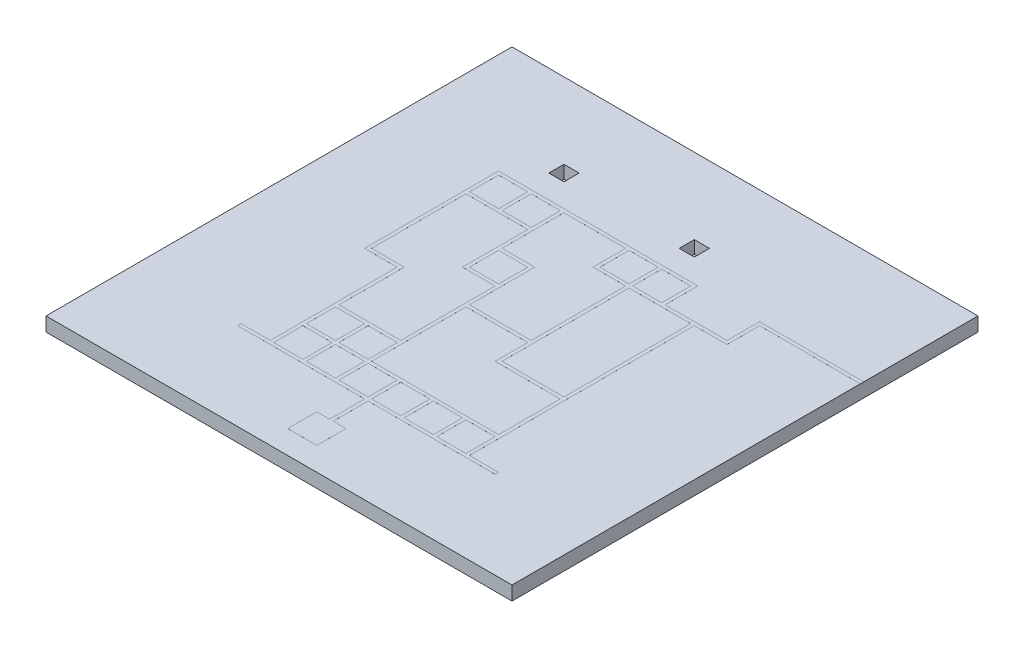
SolidWorks part; units mm, degrees
ref_plane "Front Plane" through (0, 0, 0) normal (0, 0, 1) x (1, 0, 0)
ref_plane "Top Plane" through (0, 0, 0) normal (0, 1, 0) x (1, 0, 0)
ref_plane "Right Plane" through (0, 0, 0) normal (1, 0, 0) x (0, 0, -1)
sketch "Sketch1" plane through (0, 0, 0) normal (0, 1, 0) x (1, 0, 0)
  line L0 (-3913.736, 49.4526) -> (86.264, 49.4526)
  line L5 (86.264, 49.4526) -> (86.264, -3950.5474)
  line L6 (-3913.736, 49.4526) -> (-3913.736, -3950.5474)
  line L7 (-3913.736, -3950.5474) -> (86.264, -3950.5474)
extrude "Boss-Extrude1" add sketch "Sketch1" along normal blind 120
sketch "Sketch4" plane through (0, 120, 0) normal (0, 1, 0) x (1, 0, 0)
  line L0 (-1913.736, -3950.5474) -> (-1913.736, -3750.5474)
  line L1 (-3913.736, -3950.5474) -> (86.264, -3950.5474) construction
  line L2 (-1913.736, -3750.5474) -> (-1788.736, -3750.5474)
  line L3 (-1788.736, -3750.5474) -> (-1788.736, -3500.5474)
  line L4 (-1788.736, -3500.5474) -> (-2038.736, -3500.5474)
  line L5 (-2038.736, -3500.5474) -> (-2038.736, -3750.5474)
  line L6 (-2038.736, -3750.5474) -> (-1913.736, -3750.5474)
extrude "Start" add sketch "Sketch4" along normal blind 0.1 contours L5 L6 L2 L3 L4
sketch "Sketch5" plane through (0, 120, 0) normal (0, 1, 0) x (1, 0, 0)
  line L0 (-1913.736, -3500.5474) -> (-1913.736, -3200.5474)
  line L1 (-1788.736, -3500.5474) -> (-2038.736, -3500.5474) construction
  line L2 (-1913.736, -3200.5474) -> (-1898.736, -3200.5474)
  line L3 (-1898.736, -3200.5474) -> (-1898.736, -3500.5474)
  line L4 (-1788.736, -3500.5474) -> (-2038.736, -3500.5474) construction
  line L5 (-1913.736, -3200.5474) -> (-1928.736, -3200.5474)
  line L6 (-1928.736, -3200.5474) -> (-1928.736, -3500.5474)
  line L7 (-1928.736, -3500.5474) -> (-1898.736, -3500.5474)
  line L8 (-1913.736, -3233.358) -> (-1913.736, -3239.7807)
  line L9 (-1928.736, -3200.5474) -> (-1928.736, -3170.5474)
  line L10 (-1928.736, -3170.5474) -> (-1898.736, -3170.5474)
  line L11 (-1898.736, -3170.5474) -> (-1898.736, -3200.5474)
  line L12 (-1928.736, -3200.5474) -> (-3018.736, -3200.5474)
  line L13 (-3018.736, -3200.5474) -> (-3018.736, -3170.5474)
  line L14 (-3018.736, -3170.5474) -> (-1928.736, -3170.5474)
  line L15 (-1898.736, -3200.5474) -> (-808.736, -3200.5474)
  line L16 (-808.736, -3200.5474) -> (-808.736, -3170.5474)
  line L17 (-808.736, -3170.5474) -> (-1898.736, -3170.5474)
  line L18 (-1928.736, -3500.5474) -> (-1898.736, -3500.5474)
  line M7 (-2038.736, -3500.5474) -> (-1788.736, -3500.5474)
extrude "First line" add sketch "Sketch5" along normal blind 0.1 contours L16 L17 L11 L15 | L14 L13 L12 L9 | L5 L6 L0 M7 | L3 L2 L0 M7 | L11 L10 L9 L5 L2
sketch "Sketch7" plane through (0, 120, 0) normal (0, 1, 0) x (1, 0, 0)
  line L0 (-3018.736, -3170.5474) -> (-2768.736, -3170.5474)
  line L1 (-808.736, -3170.5474) -> (-3018.736, -3170.5474) construction
  line L2 (-2768.736, -3170.5474) -> (-2768.736, -2890.5474)
  line L3 (-2768.736, -2890.5474) -> (-2738.736, -2890.5474)
  line L4 (-2738.736, -2890.5474) -> (-2738.736, -3170.5474)
  line L5 (-2738.736, -2890.5474) -> (-2488.736, -2890.5474)
  line L6 (-2488.736, -2890.5474) -> (-2488.736, -3170.5474)
  line L7 (-2488.736, -3170.5474) -> (-2458.736, -3170.5474)
  line L8 (-808.736, -3170.5474) -> (-3018.736, -3170.5474) construction
  line L9 (-2458.736, -3170.5474) -> (-2458.736, -2890.5474)
  line L10 (-2768.736, -2890.5474) -> (-2768.736, -2920.5474)
  line L11 (-2768.736, -2920.5474) -> (-2458.736, -2920.5474)
  line L12 (-2488.736, -2890.5474) -> (-2458.736, -2890.5474)
  line L13 (-2458.736, -3170.5474) -> (-2208.736, -3170.5474)
  line L14 (-2208.736, -3170.5474) -> (-2208.736, -2920.5474)
  line L15 (-2208.736, -2920.5474) -> (-2458.736, -2920.5474)
  line L16 (-2458.736, -2890.5474) -> (-2208.736, -2890.5474)
  line L17 (-2208.736, -2890.5474) -> (-2178.736, -2890.5474)
  line L18 (-2178.736, -2890.5474) -> (-2178.736, -3170.5474)
  line L19 (-2178.736, -3170.5474) -> (-1928.736, -3170.5474)
  line L20 (-1928.736, -3170.5474) -> (-1928.736, -2920.5474)
  line L21 (-1928.736, -2920.5474) -> (-2208.736, -2920.5474)
  line L22 (-1928.736, -2920.5474) -> (-1928.736, -2890.5474)
  line L23 (-1928.736, -2890.5474) -> (-2178.736, -2890.5474)
  line L24 (-1928.736, -2890.5474) -> (-1898.736, -2890.5474)
  line L25 (-1898.736, -2890.5474) -> (-1898.736, -3170.5474)
  line L26 (-2208.736, -2920.5474) -> (-2208.736, -2890.5474)
  line L27 (-1928.736, -2920.5474) -> (-1898.736, -2920.5474)
  line L28 (-1898.736, -2890.5474) -> (-1648.736, -2890.5474)
  line L29 (-1648.736, -2890.5474) -> (-1618.736, -2890.5474)
  line L30 (-1618.736, -2890.5474) -> (-1618.736, -3170.5474)
  line L31 (-1618.736, -3170.5474) -> (-1648.736, -3170.5474)
  line L32 (-1648.736, -3170.5474) -> (-1648.736, -2920.5474)
  line L33 (-1648.736, -2920.5474) -> (-1898.736, -2920.5474)
  line L34 (-1648.736, -2890.5474) -> (-1648.736, -2920.5474)
  line L35 (-1648.736, -2920.5474) -> (-1618.736, -2920.5474)
  line L36 (-1618.736, -2890.5474) -> (-1368.736, -2890.5474)
  line L37 (-1368.736, -2890.5474) -> (-1338.736, -2890.5474)
  line L38 (-1338.736, -2890.5474) -> (-1338.736, -3170.5474)
  line L39 (-1338.736, -3170.5474) -> (-1368.736, -3170.5474)
  line L40 (-1368.736, -3170.5474) -> (-1368.736, -2920.5474)
  line L41 (-1368.736, -2920.5474) -> (-1618.736, -2920.5474)
  line L42 (-1368.736, -2890.5474) -> (-1368.736, -2920.5474)
  line L43 (-1338.736, -2920.5474) -> (-1368.736, -2920.5474)
  line L44 (-1338.736, -2890.5474) -> (-1088.736, -2890.5474)
  line L45 (-1088.736, -2890.5474) -> (-1058.736, -2890.5474)
  line L46 (-1058.736, -2890.5474) -> (-1058.736, -3170.5474)
  line L47 (-1058.736, -3170.5474) -> (-1088.736, -3170.5474)
  line L48 (-1088.736, -3170.5474) -> (-1088.736, -2920.5474)
  line L49 (-1088.736, -2920.5474) -> (-1338.736, -2920.5474)
  line L50 (-1088.736, -2890.5474) -> (-1088.736, -2920.5474)
  line L51 (-1088.736, -2920.5474) -> (-1058.736, -2920.5474)
  line L52 (-2768.736, -3170.5474) -> (-2738.736, -3170.5474)
  line L53 (-2488.736, -3170.5474) -> (-2458.736, -3170.5474)
  line L54 (-2208.736, -3170.5474) -> (-2178.736, -3170.5474)
  line L55 (-1928.736, -3170.5474) -> (-1898.736, -3170.5474)
  line L56 (-1648.736, -3170.5474) -> (-1618.736, -3170.5474)
  line L57 (-1368.736, -3170.5474) -> (-1338.736, -3170.5474)
  line L58 (-1088.736, -3170.5474) -> (-1058.736, -3170.5474)
  line L59 (-2488.736, -3170.5474) -> (-2458.736, -3170.5474)
  line L60 (-2208.736, -3170.5474) -> (-2178.736, -3170.5474)
  line L61 (-1928.736, -3170.5474) -> (-1898.736, -3170.5474)
  line L62 (-1648.736, -3170.5474) -> (-1618.736, -3170.5474)
  line L63 (-1368.736, -3170.5474) -> (-1338.736, -3170.5474)
  line M9 (-3018.736, -3170.5474) -> (-808.736, -3170.5474)
extrude "First set of grids" add sketch "Sketch7" along normal blind 0.1 contours L11 L2 L4 M9 | L2 L11 L4 L3 | L4 L11 L6 L5 | L12 L6 L11 L9 | L11 L6 L9 M9 | L15 L26 L16 L9 | L26 L21 L18 L17 | L18 L21 L14 M9 | L22 L23 L18 L21 | L22 L27 L25 L24 | L34 L28 L25 L33 | L27 L20 L25 M9 | L42 L36 L30 L41 | L34 L35 L30 L29 | L35 L32 L30 M9 | L43 L38 L37 L42 | L38 L43 L40 M9 | L50 L44 L38 L49 | L50 L51 L46 L45 | L51 L48 L46 M9
sketch "Sketch9" plane through (0, 120, 0) normal (0, 1, 0) x (1, 0, 0)
  line L0 (-2768.736, -2890.5474) -> (-2768.736, -2640.5474)
  line L1 (-2768.736, -2640.5474) -> (-2738.736, -2640.5474)
  line L2 (-2738.736, -2640.5474) -> (-2738.736, -2610.5474)
  line L3 (-2738.736, -2610.5474) -> (-2768.736, -2610.5474)
  line L4 (-2768.736, -2610.5474) -> (-2768.736, -2640.5474)
  line L5 (-2738.736, -2640.5474) -> (-2738.736, -2890.5474)
  line L6 (-2768.736, -2890.5474) -> (-1058.736, -2890.5474) construction
  line L7 (-2768.736, -2610.5474) -> (-2768.736, -2640.5474)
  line L8 (-2768.736, -2890.5474) -> (-2738.736, -2890.5474)
  line L9 (-2768.736, -2890.5474) -> (-2768.736, -2640.5474)
  line L10 (-2768.736, -2613.4038) -> (-2768.736, -2640.5474)
  line L11 (-2768.736, -2890.5474) -> (-2768.736, -2640.5474)
  line L12 (-2738.736, -2640.5474) -> (-2488.736, -2640.5474)
  line L13 (-2488.736, -2640.5474) -> (-2488.736, -2890.5474)
  line L14 (-2488.736, -2890.5474) -> (-2458.736, -2890.5474)
  line L15 (-2768.736, -2890.5474) -> (-1058.736, -2890.5474) construction
  line L16 (-2458.736, -2890.5474) -> (-2458.736, -2640.5474)
  line L17 (-2458.736, -2640.5474) -> (-2488.736, -2640.5474)
  line L18 (-2458.736, -2640.5474) -> (-2458.736, -2610.5474)
  line L19 (-2458.736, -2610.5474) -> (-2738.736, -2610.5474)
  line L20 (-2488.736, -2640.5474) -> (-2488.736, -2610.5474)
  line L21 (-2458.736, -2640.5474) -> (-2208.736, -2640.5474)
  line L22 (-2208.736, -2640.5474) -> (-2208.736, -2890.5474)
  line L23 (-2208.736, -2890.5474) -> (-2178.736, -2890.5474)
  line L24 (-2178.736, -2890.5474) -> (-2178.736, -2640.5474)
  line L25 (-2178.736, -2640.5474) -> (-2208.736, -2640.5474)
  line L26 (-2178.736, -2640.5474) -> (-2178.736, -2610.5474)
  line L27 (-2178.736, -2610.5474) -> (-2208.736, -2610.5474)
  line L28 (-2208.736, -2610.5474) -> (-2208.736, -2640.5474)
  line L29 (-2208.736, -2610.5474) -> (-2458.736, -2610.5474)
  line L30 (-1058.736, -2890.5474) -> (-1058.736, -2640.5474)
  line L31 (-1058.736, -2640.5474) -> (-1058.736, -2610.5474)
  line L32 (-1058.736, -2610.5474) -> (-1088.736, -2610.5474)
  line L33 (-1088.736, -2610.5474) -> (-1088.736, -2640.5474)
  line L34 (-1088.736, -2640.5474) -> (-1088.736, -2890.5474)
  line L35 (-1088.736, -2640.5474) -> (-1058.736, -2640.5474)
  line L36 (-2768.736, -2890.5474) -> (-2738.736, -2890.5474)
  line L37 (-2768.736, -2640.5474) -> (-2768.736, -2890.5474)
  line L38 (-2488.736, -2890.5474) -> (-2458.736, -2890.5474)
  line L39 (-2208.736, -2890.5474) -> (-2178.736, -2890.5474)
  line L40 (-1088.736, -2890.5474) -> (-1058.736, -2890.5474)
  line M16 (-2768.736, -2890.5474) -> (-1058.736, -2890.5474)
extrude "Second Set of grids" add sketch "Sketch9" along normal blind 0.1 contours L5 L1 L0 M16 | L3 L4 L7 L1 L2 | L12 L20 L19 L2 | L20 L17 L18 L19 | L16 L17 L13 M16 | L28 L29 L18 L21 | L27 L28 L25 L26 | L24 L25 L22 M16 | L35 L34 L30 M16 | L33 L35 L31 L32
sketch "Sketch10" plane through (0, 120, 0) normal (0, 1, 0) x (1, 0, 0)
  line L0 (-2768.736, -2610.5474) -> (-2768.736, -2360.5474)
  line L1 (-2768.736, -2360.5474) -> (-2768.736, -2330.5474)
  line L2 (-2768.736, -2330.5474) -> (-2738.736, -2330.5474)
  line L3 (-2738.736, -2330.5474) -> (-2738.736, -2610.5474)
  line L4 (-2178.736, -2610.5474) -> (-2768.736, -2610.5474) construction
  line L5 (-2738.736, -2610.5474) -> (-2768.736, -2610.5474)
  line L6 (-2768.736, -2360.5474) -> (-2738.736, -2360.5474)
  line L7 (-2178.736, -2610.5474) -> (-2178.736, -2360.5474)
  line L8 (-2178.736, -2360.5474) -> (-2178.736, -2330.5474)
  line L9 (-2178.736, -2330.5474) -> (-2208.736, -2330.5474)
  line L10 (-2208.736, -2330.5474) -> (-2208.736, -2360.5474)
  line L11 (-2208.736, -2360.5474) -> (-2208.736, -2610.5474)
  line L12 (-2208.736, -2610.5474) -> (-2178.736, -2610.5474)
  line L13 (-2208.736, -2360.5474) -> (-2178.736, -2360.5474)
  line L14 (-1058.736, -2610.5474) -> (-1058.736, -2360.5474)
  line L15 (-1058.736, -2360.5474) -> (-1058.736, -2330.5474)
  line L16 (-1058.736, -2330.5474) -> (-1088.736, -2330.5474)
  line L17 (-1088.736, -2330.5474) -> (-1088.736, -2360.5474)
  line L18 (-1088.736, -2360.5474) -> (-1058.736, -2360.5474)
  line L19 (-1088.736, -2360.5474) -> (-1088.736, -2610.5474)
  line L20 (-1088.736, -2610.5474) -> (-1058.736, -2610.5474)
  line L21 (-1088.736, -2360.5474) -> (-1338.736, -2360.5474)
  line L22 (-1338.736, -2360.5474) -> (-1368.736, -2360.5474)
  line L23 (-1368.736, -2360.5474) -> (-1368.736, -2330.5474)
  line L24 (-1368.736, -2330.5474) -> (-1338.736, -2330.5474)
  line L25 (-1338.736, -2330.5474) -> (-1338.736, -2360.5474)
  line L26 (-1338.736, -2330.5474) -> (-1088.736, -2330.5474)
  line L27 (-1368.736, -2330.5474) -> (-1618.736, -2330.5474)
  line L28 (-1618.736, -2330.5474) -> (-1648.736, -2330.5474)
  line L29 (-1648.736, -2330.5474) -> (-1648.736, -2360.5474)
  line L30 (-1648.736, -2360.5474) -> (-1618.736, -2360.5474)
  line L31 (-1618.736, -2360.5474) -> (-1618.736, -2330.5474)
  line L32 (-1618.736, -2360.5474) -> (-1368.736, -2360.5474)
  line L33 (-1088.736, -2360.5474) -> (-1088.736, -2610.5474)
  line L34 (-1058.736, -2610.5474) -> (-1058.736, -2360.5474)
  line L35 (-1058.736, -2330.5474) -> (-1088.736, -2330.5474)
  line L36 (-1088.736, -2360.5474) -> (-1338.736, -2360.5474)
  line L37 (-1338.736, -2330.5474) -> (-1088.736, -2330.5474)
  line L38 (-1338.736, -2330.5474) -> (-1338.736, -2360.5474)
  line L39 (-1368.736, -2360.5474) -> (-1368.736, -2330.5474)
  line L40 (-1618.736, -2330.5474) -> (-1648.736, -2330.5474)
  line L41 (-1648.736, -2360.5474) -> (-1618.736, -2360.5474)
  line L42 (-1618.736, -2330.5474) -> (-1368.736, -2330.5474)
  line L43 (-1368.736, -2360.5474) -> (-1618.736, -2360.5474)
  line L44 (-2178.736, -2610.5474) -> (-2178.736, -2360.5474)
  line L45 (-2178.736, -2330.5474) -> (-2178.736, -2360.5474)
  line L46 (-2208.736, -2610.5474) -> (-2208.736, -2360.5474)
  line L47 (-2178.736, -2360.5474) -> (-2178.736, -2330.5474)
  line L48 (-2208.736, -2330.5474) -> (-2208.736, -2360.5474)
  line L49 (-2738.736, -2610.5474) -> (-2768.736, -2610.5474)
  line L50 (-2768.736, -2360.5474) -> (-2768.736, -2330.5474)
  line L51 (-2738.736, -2330.5474) -> (-2738.736, -2360.5474)
  line L52 (-1618.736, -2360.5474) -> (-1368.736, -2360.5474)
  line L53 (-1368.736, -2330.5474) -> (-1618.736, -2330.5474)
  line L54 (-1338.736, -2330.5474) -> (-1088.736, -2330.5474)
  line L55 (-1088.736, -2360.5474) -> (-1338.736, -2360.5474)
  line L56 (-1088.736, -2360.5474) -> (-1058.736, -2360.5474)
  line L57 (-1058.736, -2610.5474) -> (-1088.736, -2610.5474)
  line M5 (-1088.736, -2610.5474) -> (-1058.736, -2610.5474)
  line M21 (-2768.736, -2610.5474) -> (-2178.736, -2610.5474)
extrude "Third Set" add sketch "Sketch10" along normal blind 0.1 contours L1 L6 L3 L2 | L10 L13 L8 L9 | L13 L11 L7 M21 | L31 L32 L23 L27 | L30 L31 L28 L29 | L25 L24 L23 L22 | L26 L25 L21 L17 | L17 L18 L15 L16 | L18 L19 L14 M5 | L6 L0 L3 M21
sketch "Sketch13" plane through (0, 120, 0) normal (0, 1, 0) x (1, 0, 0)
  line L0 (-2768.736, -2330.5474) -> (-2768.736, -2080.5474)
  line L1 (-2768.736, -2080.5474) -> (-2768.736, -2050.5474)
  line L2 (-2768.736, -2050.5474) -> (-2738.736, -2050.5474)
  line L3 (-2738.736, -2050.5474) -> (-2738.736, -2080.5474)
  line L4 (-2738.736, -2080.5474) -> (-2768.736, -2080.5474)
  line L5 (-2738.736, -2080.5474) -> (-2738.736, -2330.5474)
  line L6 (-2738.736, -2330.5474) -> (-2768.736, -2330.5474)
  line L7 (-2768.736, -2050.5474) -> (-3018.736, -2050.5474)
  line L8 (-3018.736, -2050.5474) -> (-3048.736, -2050.5474)
  line L9 (-3048.736, -2050.5474) -> (-3048.736, -2080.5474)
  line L10 (-3048.736, -2080.5474) -> (-3018.736, -2080.5474)
  line L11 (-3018.736, -2080.5474) -> (-3018.736, -2050.5474)
  line L12 (-3018.736, -2080.5474) -> (-2768.736, -2080.5474)
  line L13 (-2768.736, -2330.5474) -> (-2768.736, -2080.5474)
  line L14 (-2208.736, -2330.5474) -> (-2208.736, -2080.5474)
  line L15 (-2208.736, -2080.5474) -> (-2208.736, -2050.5474)
  line L16 (-2208.736, -2050.5474) -> (-2178.736, -2050.5474)
  line L17 (-2178.736, -2050.5474) -> (-2178.736, -2080.5474)
  line L18 (-2178.736, -2080.5474) -> (-2208.736, -2080.5474)
  line L19 (-2178.736, -2080.5474) -> (-2178.736, -2330.5474)
  line L20 (-2178.736, -2330.5474) -> (-2208.736, -2330.5474) construction
  line L21 (-2178.736, -2330.5474) -> (-2208.736, -2330.5474)
  line L22 (-1648.736, -2330.5474) -> (-1648.736, -2080.5474)
  line L23 (-1648.736, -2080.5474) -> (-1648.736, -2050.5474)
  line L24 (-1648.736, -2050.5474) -> (-1618.736, -2050.5474)
  line L25 (-1618.736, -2050.5474) -> (-1618.736, -2080.5474)
  line L26 (-1618.736, -2080.5474) -> (-1648.736, -2080.5474)
  line L27 (-1618.736, -2080.5474) -> (-1618.736, -2330.5474)
  line L28 (-1058.736, -2330.5474) -> (-1648.736, -2330.5474) construction
  line L29 (-1618.736, -2330.5474) -> (-1648.736, -2330.5474)
  line L30 (-2178.736, -2080.5474) -> (-1928.736, -2080.5474)
  line L31 (-1928.736, -2080.5474) -> (-1898.736, -2080.5474)
  line L32 (-1898.736, -2080.5474) -> (-1648.736, -2080.5474)
  line L33 (-1648.736, -2050.5474) -> (-1898.736, -2050.5474)
  line L34 (-1898.736, -2050.5474) -> (-1928.736, -2050.5474)
  line L35 (-1928.736, -2050.5474) -> (-2178.736, -2050.5474)
  line L36 (-1928.736, -2050.5474) -> (-1928.736, -2080.5474)
  line L37 (-1898.736, -2050.5474) -> (-1898.736, -2080.5474)
  line L38 (-1058.736, -2330.5474) -> (-1058.736, -2080.5474)
  line L39 (-1058.736, -2080.5474) -> (-1058.736, -2050.5474)
  line L40 (-1058.736, -2050.5474) -> (-1088.736, -2050.5474)
  line L41 (-1088.736, -2050.5474) -> (-1088.736, -2080.5474)
  line L42 (-1088.736, -2080.5474) -> (-1058.736, -2080.5474)
  line L43 (-1088.736, -2080.5474) -> (-1088.736, -2330.5474)
  line L44 (-1058.736, -2330.5474) -> (-1648.736, -2330.5474) construction
  line L45 (-1088.736, -2330.5474) -> (-1058.736, -2330.5474)
  line M8 (-1648.736, -2330.5474) -> (-1058.736, -2330.5474)
  line M24 (-2768.736, -2330.5474) -> (-2738.736, -2330.5474)
  line M28 (-2208.736, -2330.5474) -> (-2178.736, -2330.5474)
extrude "4th set" add sketch "Sketch13" along normal blind 0.1 contours L10 L11 L8 L9 | L11 L12 L1 L7 | L4 L3 L2 L1 | L5 L4 L0 M24 | L19 L18 L14 M28 | L18 L17 L16 L15 | L36 L35 L17 L30 | L33 L37 L32 L23 | L37 L34 L36 L31 | L26 L25 L24 L23 | L27 L26 L22 M8 | L42 L43 L38 M8 | L41 L42 L39 L40
sketch "Sketch14" plane through (0, 120, 0) normal (0, 1, 0) x (1, 0, 0)
  line L0 (-3048.736, -2050.5474) -> (-3048.736, -1800.5474)
  line L1 (-3048.736, -1800.5474) -> (-3048.736, -1770.5474)
  line L2 (-3048.736, -1770.5474) -> (-3018.736, -1770.5474)
  line L3 (-3018.736, -1770.5474) -> (-3018.736, -1800.5474)
  line L4 (-3018.736, -1800.5474) -> (-3048.736, -1800.5474)
  line L5 (-3018.736, -1800.5474) -> (-3018.736, -2050.5474)
  line L6 (-2738.736, -2050.5474) -> (-3048.736, -2050.5474) construction
  line L7 (-3018.736, -2050.5474) -> (-3048.736, -2050.5474)
  line L8 (-2208.736, -2050.5474) -> (-2208.736, -1800.5474)
  line L9 (-2208.736, -1800.5474) -> (-2208.736, -1770.5474)
  line L10 (-2208.736, -1770.5474) -> (-2178.736, -1770.5474)
  line L11 (-2178.736, -1770.5474) -> (-2178.736, -1800.5474)
  line L12 (-2178.736, -1800.5474) -> (-2208.736, -1800.5474)
  line L13 (-2178.736, -1800.5474) -> (-2178.736, -2050.5474)
  line L14 (-2208.736, -2050.5474) -> (-1618.736, -2050.5474) construction
  line L15 (-2178.736, -2050.5474) -> (-2208.736, -2050.5474)
  line L16 (-2208.736, -1800.5474) -> (-2458.736, -1800.5474)
  line L17 (-2458.736, -1800.5474) -> (-2488.736, -1800.5474)
  line L18 (-2488.736, -1800.5474) -> (-2488.736, -1770.5474)
  line L19 (-2488.736, -1770.5474) -> (-2458.736, -1770.5474)
  line L20 (-2458.736, -1770.5474) -> (-2458.736, -1800.5474)
  line L21 (-2458.736, -1770.5474) -> (-2208.736, -1770.5474)
  line L22 (-1618.736, -2050.5474) -> (-1618.736, -1800.5474)
  line L23 (-1618.736, -1800.5474) -> (-1618.736, -1770.5474)
  line L24 (-1618.736, -1770.5474) -> (-1648.736, -1770.5474)
  line L25 (-1648.736, -1770.5474) -> (-1648.736, -1800.5474)
  line L26 (-1648.736, -1800.5474) -> (-1618.736, -1800.5474)
  line L27 (-1648.736, -1800.5474) -> (-1648.736, -2050.5474)
  line L28 (-1648.736, -2050.5474) -> (-1618.736, -2050.5474)
  line L29 (-1088.736, -2050.5474) -> (-1058.736, -2050.5474)
  line L30 (-1058.736, -2050.5474) -> (-1058.736, -1800.5474)
  line L31 (-1058.736, -1800.5474) -> (-1058.736, -1770.5474)
  line L32 (-1058.736, -1770.5474) -> (-1088.736, -1770.5474)
  line L33 (-1088.736, -1770.5474) -> (-1088.736, -1800.5474)
  line L34 (-1088.736, -1800.5474) -> (-1058.736, -1800.5474)
  line L35 (-1088.736, -1800.5474) -> (-1088.736, -2050.5474)
  line M5 (-1088.736, -2050.5474) -> (-1058.736, -2050.5474)
  line M23 (-3048.736, -2050.5474) -> (-2738.736, -2050.5474)
  line M27 (-2208.736, -2050.5474) -> (-1618.736, -2050.5474)
extrude "5th set" add sketch "Sketch14" along normal blind 0.1 contours L5 L4 L0 M23 | L4 L3 L2 L1 | L21 L20 L16 L9 | L20 L19 L18 L17 | L12 L11 L10 L9 | L13 L12 L8 M27 | L26 L27 L22 M27 | L25 L26 L23 L24 | L34 L35 L30 M5 | L33 L34 L31 L32
sketch "Sketch15" plane through (0, 120, 0) normal (0, 1, 0) x (1, 0, 0)
  line L0 (-3048.736, -1770.5474) -> (-3018.736, -1770.5474)
  line L1 (-3048.736, -1770.5474) -> (-3018.736, -1770.5474) construction
  line L2 (-3048.736, -1770.5474) -> (-3018.736, -1770.5474) construction
  line L3 (-3018.736, -1770.5474) -> (-3018.736, -1520.5474)
  line L4 (-3018.736, -1520.5474) -> (-3018.736, -1490.5474)
  line L5 (-3018.736, -1490.5474) -> (-3048.736, -1490.5474)
  line L6 (-3048.736, -1490.5474) -> (-3048.736, -1520.5474)
  line L7 (-3048.736, -1520.5474) -> (-3018.736, -1520.5474)
  line L8 (-3048.736, -1520.5474) -> (-3048.736, -1770.5474)
  line L9 (-1618.736, -1770.5474) -> (-1618.736, -1520.5474)
  line L10 (-1618.736, -1520.5474) -> (-1618.736, -1490.5474)
  line L11 (-1618.736, -1490.5474) -> (-1648.736, -1490.5474)
  line L12 (-1648.736, -1490.5474) -> (-1648.736, -1520.5474)
  line L13 (-1648.736, -1520.5474) -> (-1618.736, -1520.5474)
  line L14 (-1648.736, -1520.5474) -> (-1648.736, -1770.5474)
  line L15 (-1648.736, -1770.5474) -> (-1618.736, -1770.5474)
  line L16 (-1088.736, -1770.5474) -> (-1088.736, -1520.5474)
  line L17 (-1088.736, -1520.5474) -> (-1088.736, -1490.5474)
  line L18 (-1088.736, -1490.5474) -> (-1058.736, -1490.5474)
  line L19 (-1058.736, -1490.5474) -> (-1058.736, -1520.5474)
  line L20 (-1058.736, -1520.5474) -> (-1088.736, -1520.5474)
  line L21 (-1058.736, -1520.5474) -> (-1058.736, -1770.5474)
  line L22 (-1058.736, -1770.5474) -> (-1088.736, -1770.5474)
  line L23 (-2488.736, -1770.5474) -> (-2488.736, -1520.5474)
  line L24 (-2488.736, -1520.5474) -> (-2488.736, -1490.5474)
  line L25 (-2488.736, -1490.5474) -> (-2458.736, -1490.5474)
  line L26 (-2458.736, -1490.5474) -> (-2208.736, -1490.5474)
  line L27 (-2208.736, -1490.5474) -> (-2178.736, -1490.5474)
  line L28 (-2178.736, -1490.5474) -> (-2178.736, -1520.5474)
  line L29 (-2178.736, -1520.5474) -> (-2178.736, -1770.5474)
  line L30 (-2178.736, -1770.5474) -> (-2208.736, -1770.5474)
  line L31 (-2488.736, -1770.5474) -> (-2178.736, -1770.5474) construction
  line L32 (-2208.736, -1770.5474) -> (-2208.736, -1520.5474)
  line L33 (-2208.736, -1520.5474) -> (-2208.736, -1490.5474)
  line L34 (-2208.736, -1520.5474) -> (-2458.736, -1520.5474)
  line L35 (-2458.736, -1520.5474) -> (-2488.736, -1520.5474)
  line L36 (-2458.736, -1520.5474) -> (-2458.736, -1770.5474)
  line L37 (-2488.736, -1770.5474) -> (-2178.736, -1770.5474) construction
  line L38 (-2458.736, -1770.5474) -> (-2488.736, -1770.5474)
  line M5 (-1088.736, -1770.5474) -> (-1058.736, -1770.5474)
  line M23 (-3048.736, -1770.5474) -> (-3018.736, -1770.5474)
  line M31 (-2488.736, -1770.5474) -> (-2178.736, -1770.5474)
  line M35 (-1648.736, -1770.5474) -> (-1618.736, -1770.5474)
extrude "6th set" add sketch "Sketch15" along normal blind 0.1 contours L7 L8 L3 M23 | L6 L7 L4 L5 | L36 L35 L23 M31 | L35 L34 L33 L26 L25 L24 | L33 L32 L29 L28 L27 M31 | L13 L14 L9 M35 | L21 L20 L16 M5 | L20 L19 L18 L17 | L12 L13 L10 L11
sketch "Sketch16" plane through (0, 120, 0) normal (0, 1, 0) x (1, 0, 0)
  line L0 (-3048.736, -1490.5474) -> (-3018.736, -1490.5474)
  line L1 (-3018.736, -1490.5474) -> (-3018.736, -1240.5474)
  line L2 (-3018.736, -1240.5474) -> (-3018.736, -1210.5474)
  line L3 (-3018.736, -1210.5474) -> (-3048.736, -1210.5474)
  line L4 (-3048.736, -1210.5474) -> (-3048.736, -1240.5474)
  line L5 (-3048.736, -1240.5474) -> (-3018.736, -1240.5474)
  line L6 (-3048.736, -1240.5474) -> (-3048.736, -1490.5474)
  line L7 (-2488.736, -1490.5474) -> (-2488.736, -1240.5474)
  line L8 (-2488.736, -1240.5474) -> (-2488.736, -1210.5474)
  line L9 (-2488.736, -1210.5474) -> (-2458.736, -1210.5474)
  line L10 (-2458.736, -1210.5474) -> (-2458.736, -1240.5474)
  line L11 (-2458.736, -1240.5474) -> (-2488.736, -1240.5474)
  line L12 (-2458.736, -1240.5474) -> (-2458.736, -1490.5474)
  line L13 (-2488.736, -1490.5474) -> (-2178.736, -1490.5474) construction
  line L14 (-2458.736, -1490.5474) -> (-2488.736, -1490.5474)
  line L15 (-3018.736, -1210.5474) -> (-2768.736, -1210.5474)
  line L16 (-2768.736, -1210.5474) -> (-2738.736, -1210.5474)
  line L17 (-2738.736, -1210.5474) -> (-2488.736, -1210.5474)
  line L18 (-2488.736, -1240.5474) -> (-2738.736, -1240.5474)
  line L19 (-2738.736, -1240.5474) -> (-2768.736, -1240.5474)
  line L20 (-2768.736, -1240.5474) -> (-3018.736, -1240.5474)
  line L21 (-2768.736, -1210.5474) -> (-2768.736, -1240.5474)
  line L22 (-2738.736, -1210.5474) -> (-2738.736, -1240.5474)
  line L23 (-1648.736, -1490.5474) -> (-1618.736, -1490.5474)
  line L24 (-1618.736, -1490.5474) -> (-1618.736, -1240.5474)
  line L25 (-1618.736, -1240.5474) -> (-1618.736, -1210.5474)
  line L26 (-1618.736, -1210.5474) -> (-1648.736, -1210.5474)
  line L27 (-1648.736, -1210.5474) -> (-1648.736, -1240.5474)
  line L28 (-1648.736, -1240.5474) -> (-1618.736, -1240.5474)
  line L29 (-1648.736, -1240.5474) -> (-1648.736, -1490.5474)
  line L30 (-1088.736, -1490.5474) -> (-1088.736, -1240.5474)
  line L31 (-1088.736, -1240.5474) -> (-1088.736, -1210.5474)
  line L32 (-1088.736, -1210.5474) -> (-1058.736, -1210.5474)
  line L33 (-1058.736, -1210.5474) -> (-1058.736, -1240.5474)
  line L34 (-1058.736, -1240.5474) -> (-1088.736, -1240.5474)
  line L35 (-1058.736, -1240.5474) -> (-1058.736, -1490.5474)
  line L36 (-1058.736, -1490.5474) -> (-1088.736, -1490.5474)
  line L37 (-1058.736, -1240.5474) -> (-808.736, -1240.5474)
  line L38 (-808.736, -1240.5474) -> (-778.736, -1240.5474)
  line L39 (-778.736, -1240.5474) -> (-778.736, -1210.5474)
  line L40 (-778.736, -1210.5474) -> (-808.736, -1210.5474)
  line L41 (-808.736, -1210.5474) -> (-808.736, -1240.5474)
  line L42 (-808.736, -1210.5474) -> (-1058.736, -1210.5474)
  line L43 (-1088.736, -1210.5474) -> (-1338.736, -1210.5474)
  line L44 (-1338.736, -1210.5474) -> (-1368.736, -1210.5474)
  line L45 (-1368.736, -1210.5474) -> (-1618.736, -1210.5474)
  line L46 (-1618.736, -1240.5474) -> (-1368.736, -1240.5474)
  line L47 (-1368.736, -1240.5474) -> (-1338.736, -1240.5474)
  line L48 (-1338.736, -1240.5474) -> (-1088.736, -1240.5474)
  line L49 (-1338.736, -1210.5474) -> (-1338.736, -1240.5474)
  line L50 (-1368.736, -1210.5474) -> (-1368.736, -1240.5474)
  line L51 (-1648.736, -1240.5474) -> (-1898.736, -1240.5474)
  line L52 (-1898.736, -1240.5474) -> (-1928.736, -1240.5474)
  line L53 (-1928.736, -1240.5474) -> (-1928.736, -1210.5474)
  line L54 (-1928.736, -1210.5474) -> (-1898.736, -1210.5474)
  line L55 (-1898.736, -1210.5474) -> (-1898.736, -1240.5474)
  line L56 (-1898.736, -1210.5474) -> (-1648.736, -1210.5474)
  line M5 (-1648.736, -1490.5474) -> (-1618.736, -1490.5474)
  line M9 (-1088.736, -1490.5474) -> (-1058.736, -1490.5474)
  line M27 (-3048.736, -1490.5474) -> (-3018.736, -1490.5474)
  line M35 (-2488.736, -1490.5474) -> (-2178.736, -1490.5474)
extrude "7th set" add sketch "Sketch16" along normal blind 0.1 contours L5 L6 L1 M27 | L4 L5 L2 L3 | L21 L15 L2 L20 | L22 L16 L21 L19 | L17 L22 L18 L8 | L12 L11 L7 M35 | L11 L10 L9 L8 | L28 L29 L24 M5 | L56 L55 L51 L27 | L55 L54 L53 L52 | L27 L28 L25 L26 | L50 L45 L25 L46 | L44 L50 L47 L49 | L43 L49 L48 L31 | L41 L42 L33 L37 | L40 L41 L38 L39 | L34 L33 L32 L31 | L35 L34 L30 M9
sketch "Sketch17" plane through (0, 120, 0) normal (0, 1, 0) x (1, 0, 0)
  line L0 (-3048.736, -1210.5474) -> (-3048.736, -960.5474)
  line L1 (-3048.736, -960.5474) -> (-3048.736, -930.5474)
  line L2 (-3048.736, -930.5474) -> (-3018.736, -930.5474)
  line L3 (-3018.736, -930.5474) -> (-3018.736, -960.5474)
  line L4 (-3018.736, -960.5474) -> (-3048.736, -960.5474)
  line L5 (-3018.736, -960.5474) -> (-3018.736, -1210.5474)
  line L6 (-2458.736, -1210.5474) -> (-3048.736, -1210.5474) construction
  line L7 (-3018.736, -930.5474) -> (-2768.736, -930.5474)
  line L8 (-2768.736, -930.5474) -> (-2738.736, -930.5474)
  line L9 (-2738.736, -930.5474) -> (-2488.736, -930.5474)
  line L10 (-2488.736, -930.5474) -> (-2458.736, -930.5474)
  line L11 (-2458.736, -930.5474) -> (-2458.736, -960.5474)
  line L12 (-2458.736, -960.5474) -> (-2458.736, -1210.5474)
  line L13 (-2458.736, -1210.5474) -> (-2488.736, -1210.5474)
  line L14 (-2458.736, -1210.5474) -> (-3048.736, -1210.5474) construction
  line L15 (-2488.736, -1210.5474) -> (-2488.736, -960.5474)
  line L16 (-2488.736, -960.5474) -> (-2488.736, -930.5474)
  line L17 (-2488.736, -1210.5474) -> (-2458.736, -1210.5474)
  line L18 (-2488.736, -960.5474) -> (-2738.736, -960.5474)
  line L19 (-2738.736, -960.5474) -> (-2738.736, -930.5474)
  line L20 (-2738.736, -960.5474) -> (-2768.736, -960.5474)
  line L21 (-2768.736, -960.5474) -> (-2768.736, -930.5474)
  line L22 (-2768.736, -960.5474) -> (-3018.736, -960.5474)
  line L23 (-1928.736, -1210.5474) -> (-1928.736, -960.5474)
  line L24 (-1928.736, -960.5474) -> (-1928.736, -930.5474)
  line L25 (-1928.736, -930.5474) -> (-1898.736, -930.5474)
  line L26 (-1898.736, -930.5474) -> (-1898.736, -960.5474)
  line L27 (-1898.736, -960.5474) -> (-1898.736, -1210.5474)
  line L28 (-778.736, -1210.5474) -> (-1928.736, -1210.5474) construction
  line L29 (-1898.736, -1210.5474) -> (-1928.736, -1210.5474)
  line L30 (-1928.736, -930.5474) -> (-2178.736, -930.5474)
  line L31 (-2178.736, -930.5474) -> (-2208.736, -930.5474)
  line L32 (-2208.736, -930.5474) -> (-2458.736, -930.5474)
  line L33 (-2458.736, -960.5474) -> (-2208.736, -960.5474)
  line L34 (-2208.736, -960.5474) -> (-2178.736, -960.5474)
  line L35 (-2178.736, -960.5474) -> (-1928.736, -960.5474)
  line L36 (-2208.736, -930.5474) -> (-2208.736, -960.5474)
  line L37 (-2178.736, -930.5474) -> (-2178.736, -960.5474)
  line L38 (-2768.736, -960.5474) -> (-2768.736, -1210.5474)
  line L39 (-2768.736, -1210.5474) -> (-2738.736, -1210.5474)
  line L40 (-2738.736, -1210.5474) -> (-2738.736, -960.5474)
  line L41 (-1898.736, -930.5474) -> (-1648.736, -930.5474)
  line L42 (-1648.736, -930.5474) -> (-1618.736, -930.5474)
  line L43 (-1618.736, -930.5474) -> (-1368.736, -930.5474)
  line L44 (-1368.736, -930.5474) -> (-1338.736, -930.5474)
  line L45 (-1648.736, -930.5474) -> (-1648.736, -960.5474)
  line L46 (-1648.736, -960.5474) -> (-1898.736, -960.5474)
  line L47 (-1648.736, -960.5474) -> (-1648.736, -1210.5474)
  line L48 (-1648.736, -1210.5474) -> (-1618.736, -1210.5474)
  line L49 (-778.736, -1210.5474) -> (-1928.736, -1210.5474) construction
  line L50 (-1618.736, -1210.5474) -> (-1618.736, -960.5474)
  line L51 (-1618.736, -960.5474) -> (-1648.736, -960.5474)
  line L52 (-1618.736, -930.5474) -> (-1618.736, -960.5474)
  line L53 (-1618.736, -960.5474) -> (-1368.736, -960.5474)
  line L54 (-1368.736, -960.5474) -> (-1368.736, -930.5474)
  line L55 (-1368.736, -960.5474) -> (-1338.736, -960.5474)
  line L56 (-1338.736, -960.5474) -> (-1338.736, -930.5474)
  line L57 (-1368.736, -960.5474) -> (-1368.736, -1210.5474)
  line L58 (-1368.736, -1210.5474) -> (-1338.736, -1210.5474)
  line L59 (-1338.736, -1210.5474) -> (-1338.736, -960.5474)
  line L60 (-778.736, -1210.5474) -> (-778.736, -960.5474)
  line L61 (-778.736, -960.5474) -> (-778.736, -930.5474)
  line L62 (-778.736, -930.5474) -> (-808.736, -930.5474)
  line L63 (-808.736, -930.5474) -> (-808.736, -960.5474)
  line L64 (-808.736, -960.5474) -> (-778.736, -960.5474)
  line L65 (-808.736, -960.5474) -> (-808.736, -1210.5474)
  line L66 (-808.736, -1210.5474) -> (-778.736, -1210.5474)
  line L67 (-778.736, -930.5474) -> (86.264, -930.5474)
  line L68 (86.264, -3950.5474) -> (86.264, 49.4526) construction
  line L69 (-778.736, -960.5474) -> (86.264, -960.5474)
  line L70 (86.264, -960.5474) -> (86.264, -930.5474)
  line M19 (-3048.736, -1210.5474) -> (-2458.736, -1210.5474)
  line M27 (-1928.736, -1210.5474) -> (-778.736, -1210.5474)
  line M31 (86.264, -3950.5474) -> (86.264, 49.4526)
extrude "8th set" add sketch "Sketch17" along normal blind 0.1 contours L5 L4 L0 M19 | L4 L3 L2 L1 | L22 L21 L7 L3 | L21 L20 L19 L8 | L19 L18 L16 L9 | L40 L20 L38 M19 | L16 L15 L12 L11 L10 M19 | L36 L32 L11 L33 | L37 L31 L36 L34 | L30 L37 L35 L24 | L27 L26 L25 L24 L23 M27 | L46 L45 L41 L26 | L52 L42 L45 L51 | L50 L51 L47 M27 | L53 L54 L43 L52 | L55 L56 L44 L54 | L59 L55 L57 M27 | L64 L65 L60 M27 | L63 L64 L61 L62 | L61 L69 L67 M31
sketch "Sketch18" plane through (0, 120, 0) normal (0, 1, 0) x (1, 0, 0)
  line L0 (-2767.7991, -930.5474) -> (-2767.7991, -730.5474)
  line L1 (-3048.736, -930.5474) -> (-1338.736, -930.5474) construction
  line L2 (-2767.7991, -730.5474) -> (-2737.7991, -730.5474)
  line L3 (-2737.7991, -730.5474) -> (-2737.7991, -930.5474)
  line L4 (-3048.736, -930.5474) -> (-1338.736, -930.5474) construction
  line L5 (-2752.7991, -730.5474) -> (-2817.7991, -730.5474)
  line L6 (-2817.7991, -730.5474) -> (-2817.7991, -600.5474)
  line L7 (-2817.7991, -600.5474) -> (-2687.7991, -600.5474)
  line L8 (-2687.7991, -600.5474) -> (-2687.7991, -730.5474)
  line L9 (-2687.7991, -730.5474) -> (-2752.7991, -730.5474)
  line L11 (-1648.736, -930.5474) -> (-1648.736, -730.5474)
  line L12 (-1648.736, -730.5474) -> (-1618.736, -730.5474)
  line L13 (-1618.736, -730.5474) -> (-1618.736, -930.5474)
  line L14 (-1633.736, -730.5474) -> (-1698.736, -730.5474)
  line L15 (-1698.736, -730.5474) -> (-1698.736, -600.5474)
  line L16 (-1698.736, -600.5474) -> (-1568.736, -600.5474)
  line L17 (-1568.736, -600.5474) -> (-1568.736, -730.5474)
  line L18 (-1568.736, -730.5474) -> (-1633.736, -730.5474)
extrude "Cavities" cut sketch "Sketch18" against normal blind 110 contours L9 L8 L7 L6 L5 L2 | L18 L17 L16 L15 L14 L12
